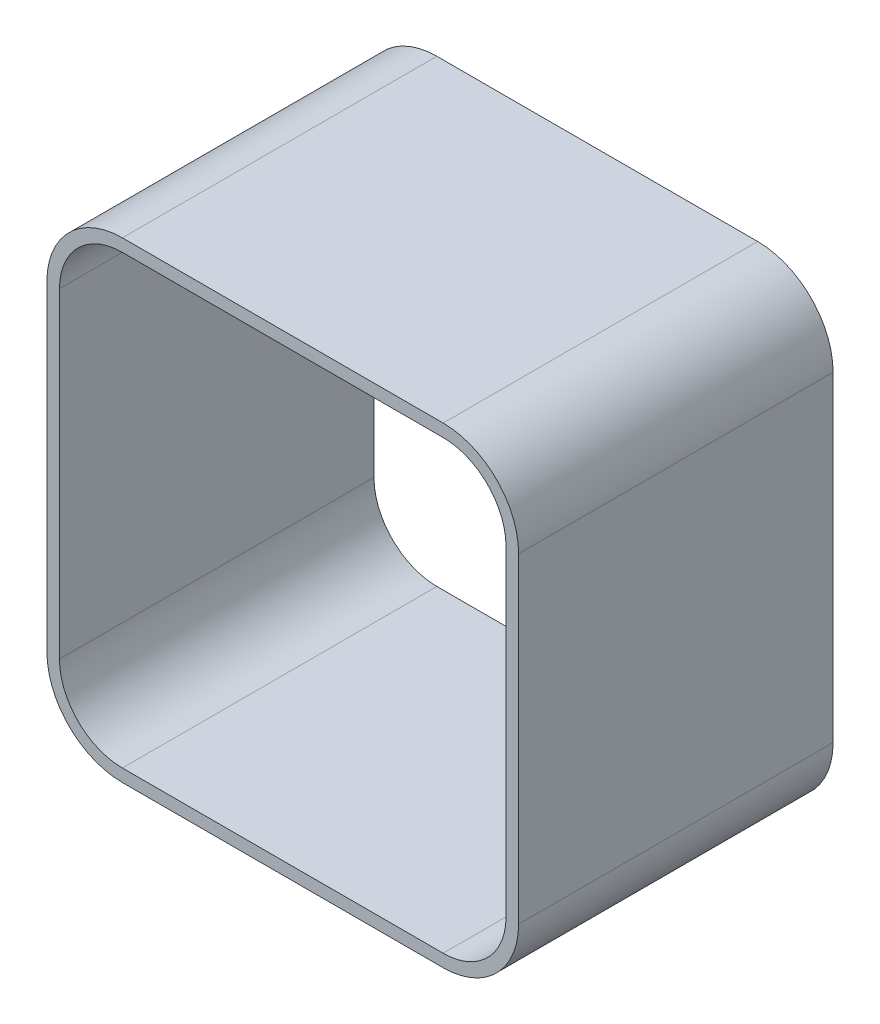
SolidWorks part; units mm, degrees
ref_plane "Front Plane" through (0, 0, 0) normal (0, 0, 1) x (1, 0, 0)
ref_plane "Top Plane" through (0, 0, 0) normal (0, 1, 0) x (1, 0, 0)
ref_plane "Right Plane" through (0, 0, 0) normal (1, 0, 0) x (0, 0, -1)
sketch "Sketch1" plane through (0, 0, 0) normal (0, 0, 1) x (1, 0, 0)
  line L1 (-7.1, 7.1) -> (7.1, 7.1)
  line L2 (-7.1, 7.1) -> (-7.1, -7.1)
  line L3 (-7.1, -7.1) -> (7.1, -7.1)
  line L4 (7.1, 7.1) -> (7.1, -7.1)
  line L5 (-7.1, 7.1) -> (7.1, -7.1) construction
  line L6 (-7.1, -7.1) -> (7.1, 7.1) construction
  line L7 (-7.5, 7.5) -> (7.5, 7.5)
  line L8 (-7.5, 7.5) -> (-7.5, -7.5)
  line L9 (-7.5, -7.5) -> (7.5, -7.5)
  line L10 (7.5, 7.5) -> (7.5, -7.5)
  line L11 (-7.5, 7.5) -> (7.5, -7.5) construction
  line L12 (-7.5, -7.5) -> (7.5, 7.5) construction
  point P0 (0, 0)
  point P7 (0, 0)
  dimension "D1" = 0.4
  dimension "D2" = 0.4
  dimension "D3" = 15
extrude "Boss-Extrude1" add sketch "Sketch1" along normal blind 10
fillet "Fillet1" radius 2 4 edges at (-7.1, -7.1, 5) (7.1, -7.1, 5) (7.1, 7.1, 5) (-7.1, 7.1, 5)
fillet "Fillet2" radius 2.4 4 edges at (7.5, -7.5, 5) (7.5, 7.5, 5) (-7.5, -7.5, 5) (-7.5, 7.5, 5)
fillet "Fillet3" [suppressed] radius 4
fillet "Fillet4" [suppressed] radius 4.4
